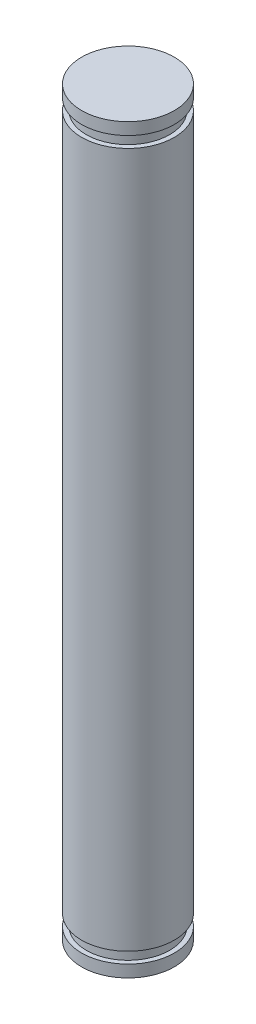
SolidWorks part; units mm, degrees
ref_plane "前视基准面" through (0, 0, 0) normal (0, 0, 1) x (1, 0, 0)
ref_plane "上视基准面" through (0, 0, 0) normal (0, 1, 0) x (1, 0, 0)
ref_plane "右视基准面" through (0, 0, 0) normal (1, 0, 0) x (0, 0, -1)
sketch "草图1" plane through (0, 0, 0) normal (0, 0, 1) x (1, 0, 0)
  line L0 (0, 0) -> (-5, 0)
  line L1 (-5, 0) -> (-5, 1.3)
  line L2 (-5, 1.3) -> (-4.5, 1.3)
  line L3 (-4.5, 1.3) -> (-4.5, 2.5)
  line L4 (-4.5, 2.5) -> (-5, 2.5)
  line L5 (-5, 2.5) -> (-5, 77.5)
  line L6 (-5, 77.5) -> (-4.5, 77.5)
  line L7 (-4.5, 77.5) -> (-4.5, 78.7)
  line L8 (-4.5, 78.7) -> (-5, 78.7)
  line L9 (-5, 78.7) -> (-5, 80)
  line L10 (-5, 80) -> (0, 80)
  line L11 (0, 80) -> (0, 0) construction
  line L12 (0, 0) -> (0, 80)
  dimension "D1" = 80
  dimension "D2" = 5
  dimension "D3" = 1.2
  dimension "D4" = 0.5
  dimension "D5" = 75
revolve "旋转1" add sketch "草图1" angle 360 about L11
